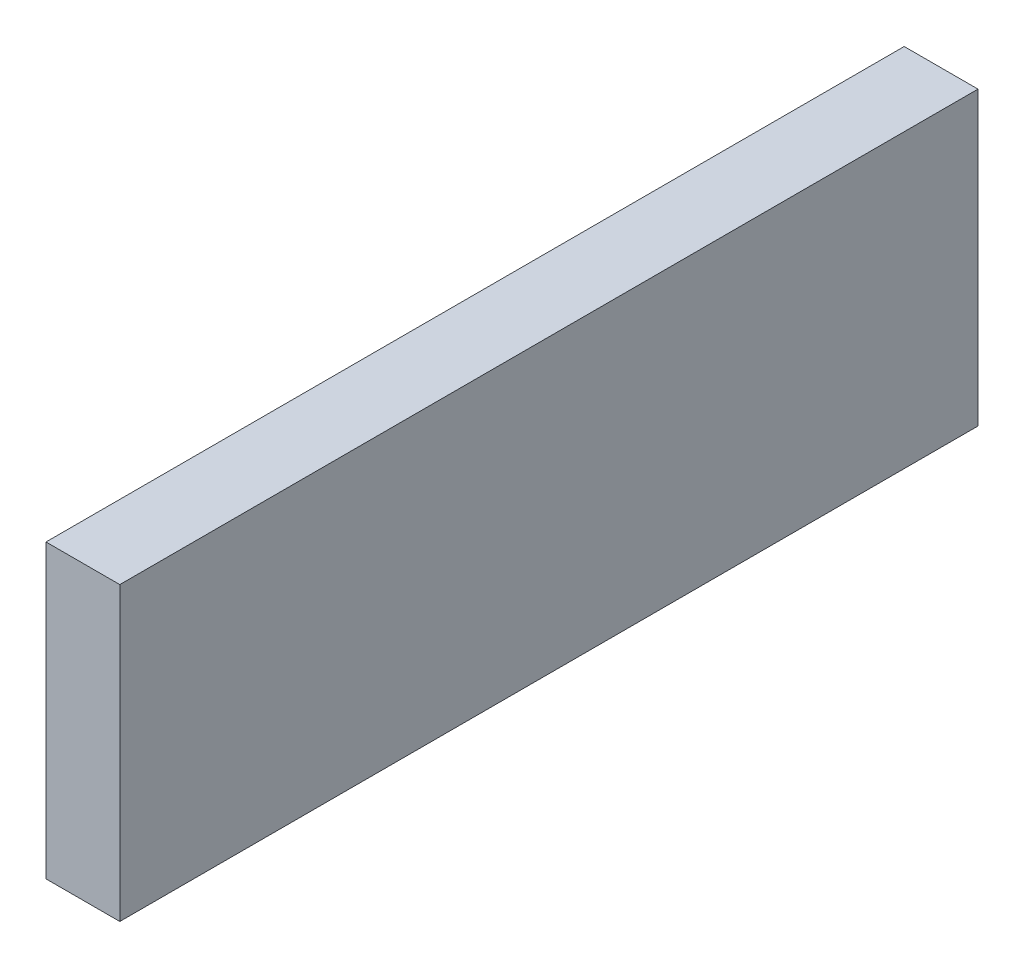
SolidWorks part; units mm, degrees
material "Pine"
ref_plane "Front Plane" through (0, 0, 0) normal (0, 0, 1) x (1, 0, 0)
ref_plane "Top Plane" through (0, 0, 0) normal (0, 1, 0) x (1, 0, 0)
ref_plane "Right Plane" through (0, 0, 0) normal (1, 0, 0) x (0, 0, -1)
sketch "Sketch1" plane through (0, 0, 0) normal (1, 0, 0) x (0, 0, -1)
  line L1 (-63.5, -21.59) -> (63.5, -21.59)
  line L2 (-63.5, -21.59) -> (-63.5, 21.59)
  line L3 (-63.5, 21.59) -> (63.5, 21.59)
  line L4 (63.5, -21.59) -> (63.5, 21.59)
  line L5 (-63.5, -21.59) -> (63.5, 21.59) construction
  line L6 (-63.5, 21.59) -> (63.5, -21.59) construction
  point P0 (0, 0)
  dimension "D1" = 127
  dimension "D2" = 43.18
extrude "Boss-Extrude1" add sketch "Sketch1" along normal blind 10.922
